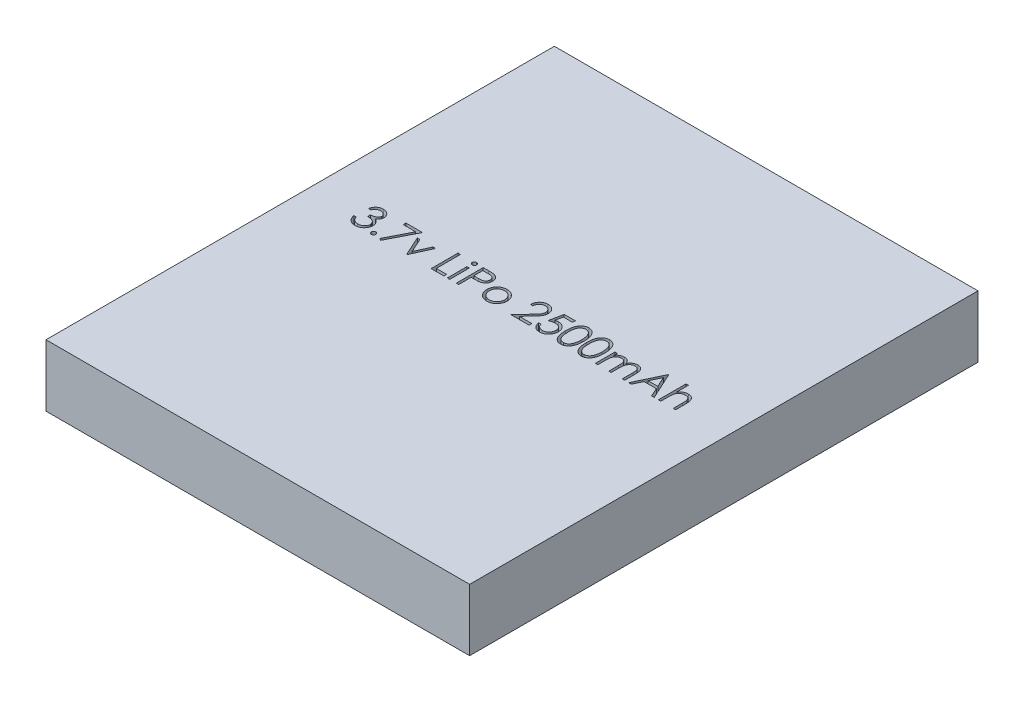
SolidWorks part; units mm, degrees
ref_plane "Front Plane" through (0, 0, 0) normal (0, 0, 1) x (1, 0, 0)
ref_plane "Top Plane" through (0, 0, 0) normal (0, 1, 0) x (1, 0, 0)
ref_plane "Right Plane" through (0, 0, 0) normal (1, 0, 0) x (0, 0, -1)
sketch "Sketch1" plane through (0, 0, 0) normal (0, 1, 0) x (1, 0, 0)
  line L1 (0, 0) -> (50, 0)
  line L2 (0, 0) -> (0, 60)
  line L3 (0, 60) -> (50, 60)
  line L4 (50, 0) -> (50, 60)
  dimension "D1" = 60
  dimension "D2" = 50
extrude "Boss-Extrude1" add sketch "Sketch1" along normal blind 7.3
sketch "Sketch2" plane through (0, 7.3, 0) normal (0, 1, 0) x (1, 0, 0)
  line L0 (5, 30) -> (45, 30) construction
  line L1 (50, 60) -> (0, 60) construction
  text T0 "3.7v LiPo 2500mAh"
  point P4 (25, 60)
  point P5 (25, 30)
  dimension "D1" = 40
extrude "Cut-Extrude4" cut sketch "Sketch2" against normal blind 1
